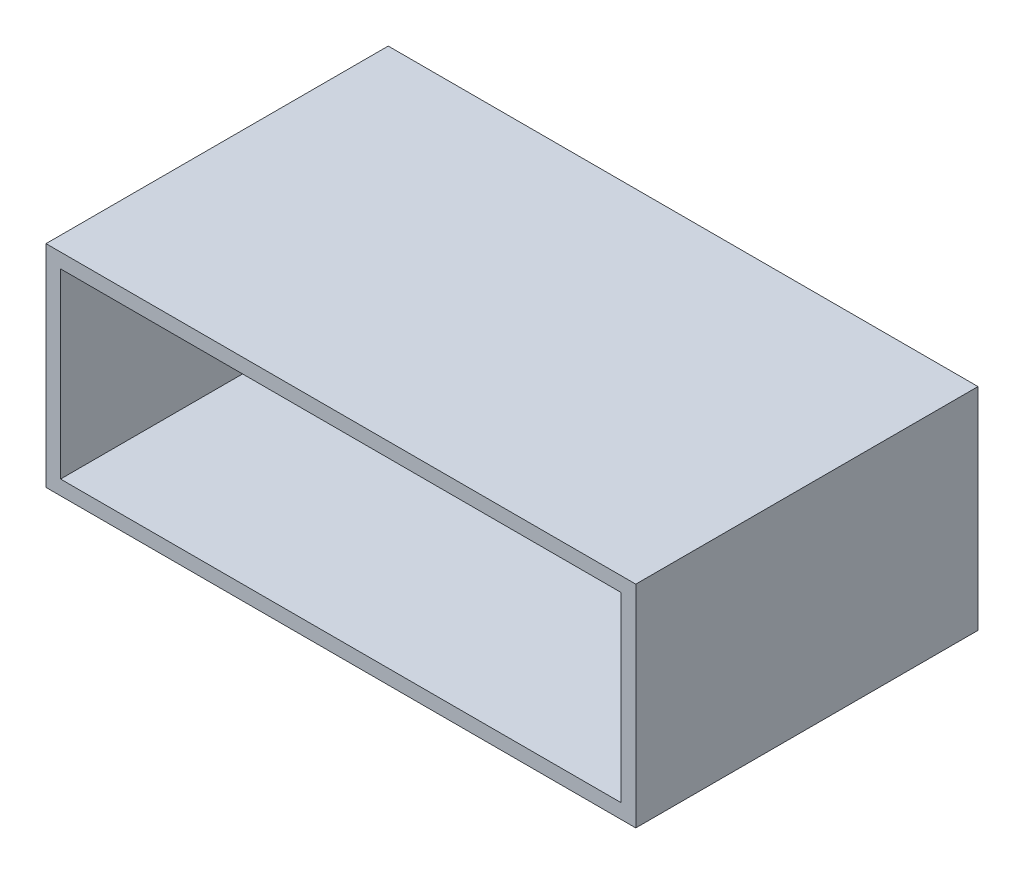
SolidWorks part; units mm, degrees
ref_plane "Front Plane" through (0, 0, 0) normal (0, 0, 1) x (1, 0, 0)
ref_plane "Top Plane" through (0, 0, 0) normal (0, 1, 0) x (1, 0, 0)
ref_plane "Right Plane" through (0, 0, 0) normal (1, 0, 0) x (0, 0, -1)
sketch "Sketch1" plane through (0, 0, 0) normal (0, 0, 1) x (1, 0, 0)
  line L1 (0, 0) -> (81, 0)
  line L2 (0, 0) -> (0, 29)
  line L3 (0, 29) -> (81, 29)
  line L4 (81, 0) -> (81, 29)
  line L6 (2, 2) -> (79, 2)
  line L7 (2, 2) -> (2, 27)
  line L8 (2, 27) -> (79, 27)
  line L9 (79, 2) -> (79, 27)
  dimension "D1" = 2
  dimension "D2" = 79
  dimension "D3" = 81
  dimension "D4" = 2
  dimension "D5" = 27
  dimension "D6" = 29
extrude "Profile" add sketch "Sketch1" along normal blind 47
sketch "Sketch2" plane through (0, 0, 0) normal (0, 0, 1) x (1, 0, 0)
  line L1 (2, 2) -> (79, 2)
  line L2 (2, 2) -> (2, 27)
  line L3 (2, 27) -> (79, 27)
  line L4 (79, 2) -> (79, 27)
  dimension "D1" = 77
  dimension "D2" = 25
extrude "Back" add sketch "Sketch2" along normal blind 2
equation "\"Profile_Depth\"= 47mm"
equation "\"D1@Profile\" = \"Profile_Depth\""
equation "\"Profile_Sketch_1\"= 2mm"
equation "\"D1@Sketch1\" = \"Profile_Sketch_1\""
equation "\"Profile_Sketch_2\"= 79mm"
equation "\"D2@Sketch1\" = \"Profile_Sketch_2\""
equation "\"Profile_Sketch_3\"= 81mm"
equation "\"D3@Sketch1\" = \"Profile_Sketch_3\""
equation "\"Profile_Sketch_4\"= 2mm"
equation "\"D4@Sketch1\" = \"Profile_Sketch_4\""
equation "\"Profile_Sketch_5\"= 27mm"
equation "\"D5@Sketch1\" = \"Profile_Sketch_5\""
equation "\"Profile_Sketch_6\"= 29mm"
equation "\"D6@Sketch1\" = \"Profile_Sketch_6\""
equation "\"Back_Depth\"= 2mm"
equation "\"D1@Back\" = \"Back_Depth\""
equation "\"Back_Sketch_1\"= 77mm"
equation "\"D1@Sketch2\" = \"Back_Sketch_1\""
equation "\"Back_Sketch_2\"= 25mm"
equation "\"D2@Sketch2\" = \"Back_Sketch_2\""
equation "\"EnvelopeWidth\"= 81mm"
equation "\"EnvelopeHeight\"= 29mm"
